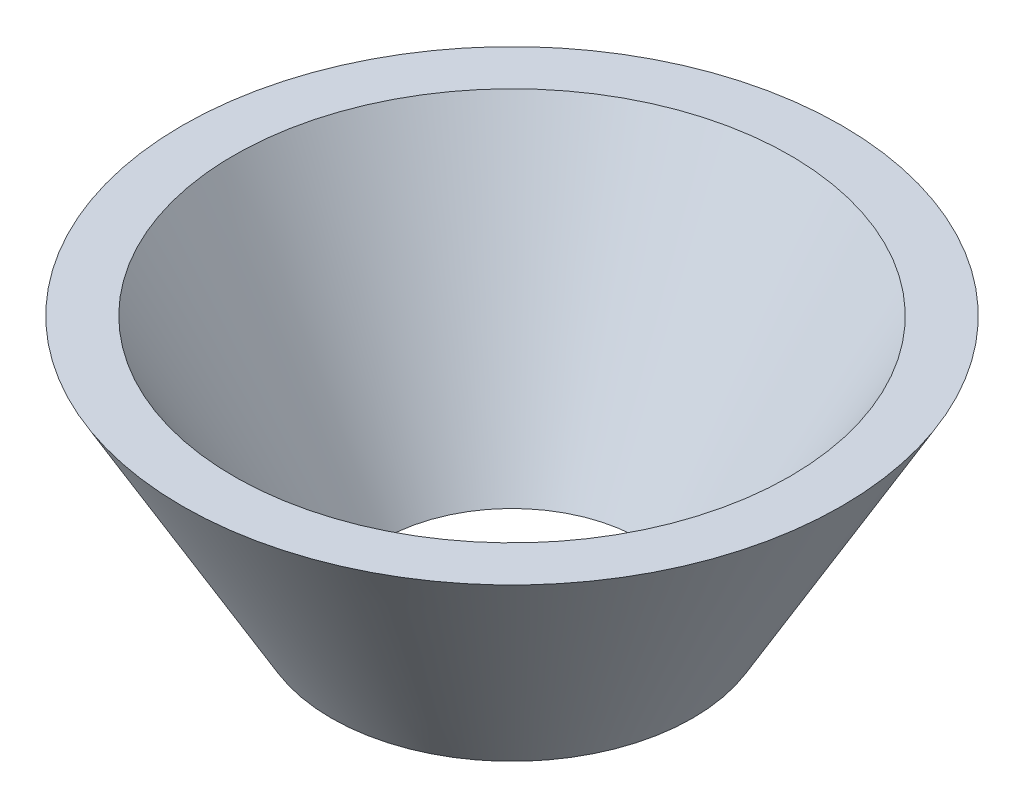
SolidWorks part; units mm, degrees
ref_plane "Front Plane" through (0, 0, 0) normal (0, 0, 1) x (1, 0, 0)
ref_plane "Top Plane" through (0, 0, 0) normal (0, 1, 0) x (1, 0, 0)
ref_plane "Right Plane" through (0, 0, 0) normal (1, 0, 0) x (0, 0, -1)
sketch "Sketch1" plane through (0, 0, 0) normal (0, 0, 1) x (1, 0, 0)
  line L0 (0, 0) -> (0, 26.5259) construction
  line L1 (25, 0) -> (-25, 0) construction
  line L2 (-25, 0) -> (-53.8675, 50)
  line L3 (-53.8675, 50) -> (-63.8675, 50)
  line L4 (-63.8675, 50) -> (-35, 0)
  line L5 (-35, 0) -> (-25, 0)
  point P7 (0, 0)
  dimension "D1" = 50
  dimension "D2" = 120
  dimension "D3" = 50
  dimension "D4" = 10
  dimension "D5" = 10
revolve "Revolve1" add sketch "Sketch1" angle 360 about L0
ref_plane "Plane1" through (60, 0, 0) normal (1, 0, 0) x (0, 0, -1)
sketch "Sketch4" plane through (0, 0, 0) normal (0, 0, 1) x (1, 0, 0)
  line L0 (0, 0) -> (0, -10)
  line L1 (18.2569, -29.9239) -> (59.0406, -33.492)
  arc A0 (0, -10) -> (18.2569, -29.9239) centre (20, -10) ccw
  point P6 (0, -48.3266)
  dimension "D3" = 20
